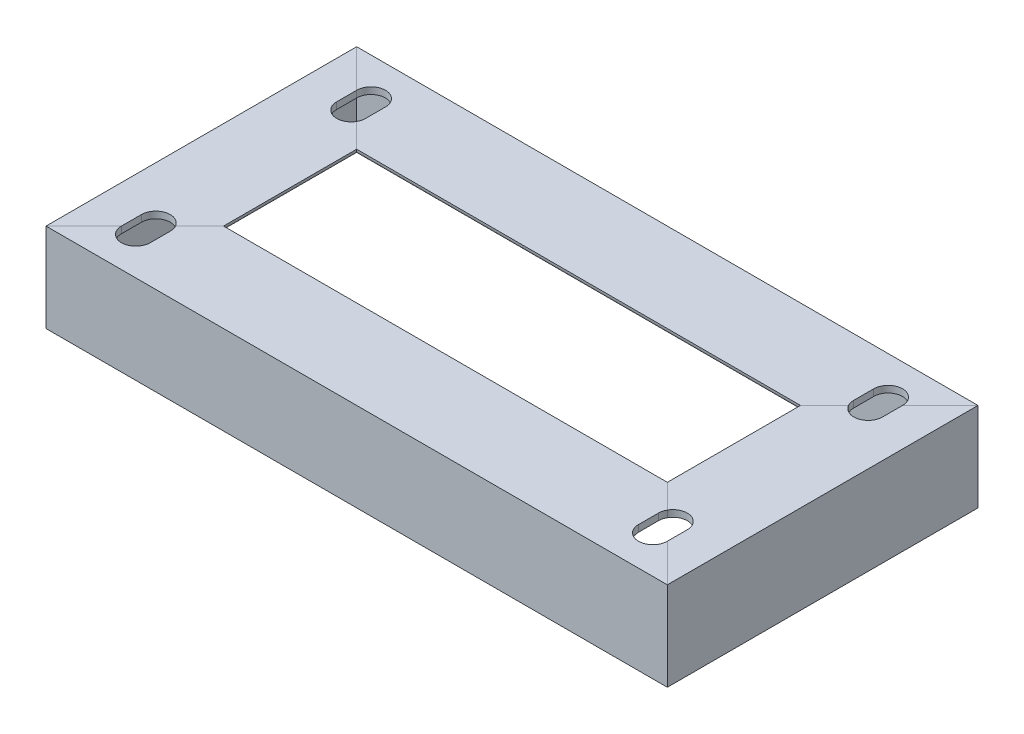
SolidWorks part; units mm, degrees
ref_plane "Front Plane" through (0, 0, 0) normal (0, 0, 1) x (1, 0, 0)
ref_plane "Top Plane" through (0, 0, 0) normal (0, 1, 0) x (1, 0, 0)
ref_plane "Right Plane" through (0, 0, 0) normal (1, 0, 0) x (0, 0, -1)
sketch3d "3DSketch2"
  line L1 (-140, 0, 70) -> (-140, 0, -70)
  line L2 (-140, 0, 70) -> (140, 0, 70)
  line L3 (140, 0, 70) -> (140, 0, -70)
  line L4 (-140, 0, -70) -> (140, 0, -70)
  line L5 (-140, 0, 70) -> (140, 0, -70) construction
  line L6 (140, 0, 70) -> (-140, 0, -70) construction
  point P0 (0, 0, 0)
  dimension "D1" = 140
  dimension "D2" = 280
other "Iron V40X40X3(1)"
ref_plane "Plane1" through (-140, 0, 70) normal (0, 0, -1) x (1, 0, 0)
sketch "Sketch1" plane through (-140, 0, 70) normal (0, 0, -1) x (1, 0, 0)
  line L0 (0, 0) -> (0, 40)
  line L1 (0, 20) -> (3, 20) construction
  line L2 (3, 37) -> (3, 6.5)
  line L3 (6.5, 3) -> (37, 3)
  line L4 (20, 3) -> (20, 0) construction
  line L5 (40, 0) -> (0, 0)
  arc A0 (40, 0) -> (37, 3) centre (37, 0) ccw
  arc A1 (0, 40) -> (3, 37) centre (0, 37) cw
  arc A2 (6.5, 3) -> (3, 6.5) centre (6.5, 6.5) cw
  point P10 (20, 0)
  point P14 (0, 20)
  point P15 (3, 20)
  point P16 (20, 3)
  point P17 (3, 40)
  point P18 (40, 3)
  point P21 (0, 0)
  dimension "D2" = 3
  dimension "D3" = 40
  dimension "Radius_1" = 3.5
  dimension "D1" = 3
sketch "Sketch2" plane through (0, 0, 0) normal (0, 1, 0) x (1, 0, 0)
  line L0 (116.5, 53) -> (116.5, 44) construction
  line L1 (123, 53) -> (123, 44)
  line L2 (110, 53) -> (110, 44)
  line L3 (-116.5, 53) -> (-116.5, 44) construction
  line L4 (-110, 53) -> (-110, 44)
  line L5 (-123, 53) -> (-123, 44)
  line L6 (-116.5, -44) -> (-116.5, -53) construction
  line L7 (-110, -44) -> (-110, -53)
  line L8 (-123, -44) -> (-123, -53)
  line L9 (116.5, -44) -> (116.5, -53) construction
  line L10 (123, -44) -> (123, -53)
  line L11 (110, -44) -> (110, -53)
  line L12 (140, -70) -> (140, 70) construction
  line L13 (140, 70) -> (-140, 70) construction
  arc A0 (123, 53) -> (110, 53) centre (116.5, 53) ccw
  arc A1 (110, 44) -> (123, 44) centre (116.5, 44) ccw
  arc A2 (-110, 53) -> (-123, 53) centre (-116.5, 53) ccw
  arc A3 (-123, 44) -> (-110, 44) centre (-116.5, 44) ccw
  arc A4 (-110, -44) -> (-123, -44) centre (-116.5, -44) ccw
  arc A5 (-123, -53) -> (-110, -53) centre (-116.5, -53) ccw
  arc A6 (123, -44) -> (110, -44) centre (116.5, -44) ccw
  arc A7 (110, -53) -> (123, -53) centre (116.5, -53) ccw
  point P2 (116.5, 48.5)
  point P12 (-116.5, 48.5)
  point P19 (-116.5, -48.5)
  point P26 (116.5, -48.5)
  dimension "D6" = 17
  dimension "D7" = 233
  dimension "D8" = 97
  dimension "D1" = 9
  dimension "D2" = 13
  dimension "D5" = 23.5
  dimension "D3" = 2
  dimension "D4" = 2
extrude "Cut-Extrude1" cut sketch "Sketch2" against normal blind 10 from offset 5
